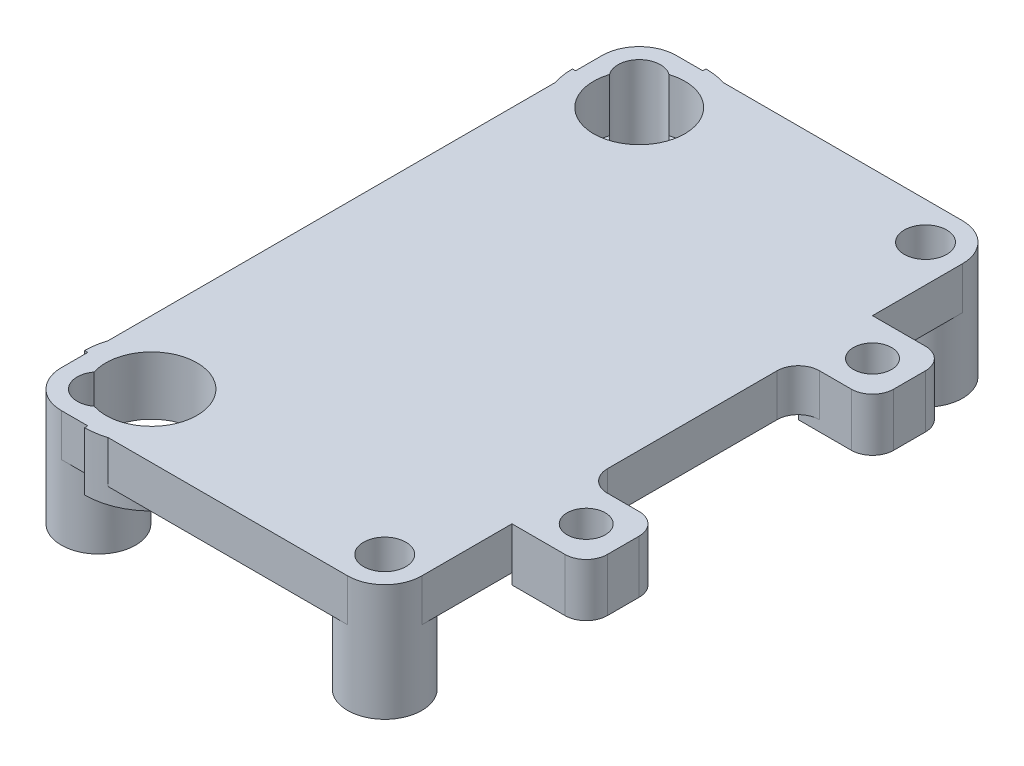
SolidWorks part; units mm, degrees
ref_plane "Front Plane" through (0, 0, 0) normal (0, 0, 1) x (1, 0, 0)
ref_plane "Top Plane" through (0, 0, 0) normal (0, 1, 0) x (1, 0, 0)
ref_plane "Right Plane" through (0, 0, 0) normal (1, 0, 0) x (0, 0, -1)
sketch "Sketch1" plane through (0, 0, 0) normal (0, 1, 0) x (1, 0, 0)
  line L1 (0, 0) -> (27, 0) construction
  line L2 (0, 0) -> (0, 51) construction
  line L3 (0, 51) -> (27, 51) construction
  line L4 (27, 0) -> (27, 51) construction
  circle A0 centre (0, 51) radius 3.5
  circle A1 centre (27, 51) radius 3.5
  circle A2 centre (27, 0) radius 3.5
  circle A3 centre (0, 0) radius 3.5
  dimension "D3" = 7
  dimension "D1" = 51
  dimension "D2" = 27
extrude "Boss-Extrude1" add sketch "Sketch1" along normal blind 11
sketch "Sketch2" plane through (0, 11, 0) normal (0, 1, 0) x (1, 0, 0)
  line L0 (27, 54.5) -> (0, 54.5)
  line L2 (-3.5, 51) -> (-3.5, 0)
  line L4 (0, -3.5) -> (27, -3.5)
  line L6 (30.5, 0) -> (30.5, 51)
  circle A0 centre (0, 0) radius 3.5 construction
  circle A1 centre (27, 0) radius 3.5 construction
  circle A2 centre (27, 51) radius 3.5 construction
  circle A3 centre (0, 51) radius 3.5 construction
  arc A4 (-3.5, 0) -> (0, -3.5) centre (0, 0) ccw
  arc A5 (27, -3.5) -> (30.5, 0) centre (27, 0) ccw
  arc A6 (30.5, 51) -> (27, 54.5) centre (27, 51) ccw
  arc A7 (0, 54.5) -> (-3.5, 51) centre (0, 51) ccw
extrude "Boss-Extrude2" add sketch "Sketch2" against normal blind 1
hole_wizard "Ø4.0mm Dowel Hole1" positions "Sketch4" profile "Sketch6" hole size "Ø4.0" standard "DIN" end condition through all
sketch "Sketch4" plane through (0, 0, 0) normal (0, -1, 0) x (-1, 0, 0)
  point P0 (-27, 51)
  point P3 (0, 51)
  point P6 (0, 0)
  point P9 (-27, 0)
sketch "Sketch6" plane through (27, 0, -51) normal (1, 0, 0) x (0, 0, -1)
  line L0 (0, 0) -> (0, 11)
  line L1 (0, 11) -> (2, 11)
  line L2 (2, 11) -> (2, 0)
  line L5 (2, 0) -> (0, 0)
  line L11 (0, -6.35) -> (0, 107.95) construction
  dimension "Thru Hole Dia." = 4
  dimension "Thru Hole Depth" = 11
sketch "Sketch10" plane through (0, 10, 0) normal (0, -1, 0) x (1, 0, 0)
  line L0 (0, 0) -> (27, -51) construction
  line L1 (27, 0) -> (0, -51) construction
  line L2 (26.1162, 0.4679) -> (-0.8838, -50.5321)
  line L3 (27.8838, -0.4679) -> (0.8838, -51.4679)
  line L4 (-0.8838, -0.4679) -> (26.1162, -51.4679)
  line L5 (0.8838, 0.4679) -> (27.8838, -50.5321)
  line L6 (-1.5, 0) -> (-1.5, -51)
  line L7 (0, -52.5) -> (27, -52.5)
  line L8 (28.5, -51) -> (28.5, 0)
  line L9 (27, 1.5) -> (0, 1.5)
  line L10 (-3.5, 0) -> (-3.5, -51)
  line L11 (27, 3.5) -> (0, 3.5)
  line L12 (30.5, -51) -> (30.5, 0)
  line L13 (0, -54.5) -> (27, -54.5)
  line L14 (-3.5, 0) -> (-3.5, -51)
  line L15 (27, 3.5) -> (0, 3.5)
  line L16 (30.5, -51) -> (30.5, 0)
  line L17 (0, -54.5) -> (27, -54.5)
  arc A0 (-1.5, -51) -> (0, -52.5) centre (0, -51) ccw
  arc A1 (27, -52.5) -> (28.5, -51) centre (27, -51) ccw
  arc A2 (28.5, 0) -> (27, 1.5) centre (27, 0) ccw
  arc A3 (0, 1.5) -> (-1.5, 0) centre (0, 0) ccw
  arc A4 (0, 3.5) -> (-3.5, 0) centre (0, 0) ccw
  arc A5 (30.5, 0) -> (27, 3.5) centre (27, 0) ccw
  arc A6 (27, -54.5) -> (30.5, -51) centre (27, -51) ccw
  arc A7 (-3.5, -51) -> (0, -54.5) centre (0, -51) ccw
  arc A8 (0, 3.5) -> (-3.5, 0) centre (0, 0) ccw
  arc A9 (30.5, 0) -> (27, 3.5) centre (27, 0) ccw
  arc A10 (27, -54.5) -> (30.5, -51) centre (27, -51) ccw
  arc A11 (-3.5, -51) -> (0, -54.5) centre (0, -51) ccw
  circle A12 centre (0, -51) radius 3.5 construction
  circle A13 centre (27, -51) radius 3.5 construction
  circle A14 centre (27, 0) radius 3.5 construction
  circle A15 centre (0, 0) radius 3.5 construction
  circle A16 centre (0, -51) radius 3.5
  circle A17 centre (27, -51) radius 3.5
  circle A18 centre (27, 0) radius 3.5
  circle A19 centre (0, 0) radius 3.5
  arc M19 (0, 3.5) -> (-3.5, 0) centre (0, 0) cw
  line M20 (-3.5, 0) -> (-3.5, -51)
  arc M21 (-3.5, -51) -> (0, -54.5) centre (0, -51) cw
  line M22 (0, -54.5) -> (27, -54.5)
  arc M23 (27, -54.5) -> (30.5, -51) centre (27, -51) cw
  line M24 (30.5, -51) -> (30.5, 0)
  arc M25 (30.5, 0) -> (27, 3.5) centre (27, 0) cw
  line M26 (27, 3.5) -> (0, 3.5)
  dimension "D1" = 1
  dimension "D2" = 1
  dimension "D3" = 1
  dimension "D4" = 1
  dimension "D5" = 0
  dimension "D6" = 2
extrude "Boss-Extrude3" add sketch "Sketch10" along normal blind 3 contours L6 M19 M20 M21 | L9 M25 M26 M19 | L5 L4 L2 M19 | L2 L5 L3 M25 | L8 M23 M24 M25 | L7 M21 M22 M23 | L5 L2 L4 L3 | L5 L3 L4 M23 | L4 L2 L3 M21
sketch "Sketch11" plane through (0, 7, 0) normal (0, -1, 0) x (1, 0, 0)
  line L0 (30.5, -8.5) -> (37.5, -8.5)
  line L1 (37.5, -8.5) -> (37.5, -15.5)
  line L2 (37.5, -15.5) -> (30.5, -15.5)
  line L3 (30.5, -51) -> (30.5, 0) construction
  line L5 (14.6315, -25.5) -> (41.7794, -25.5) construction
  line L6 (37.5, -35.5) -> (30.5, -35.5)
  line L7 (37.5, -42.5) -> (37.5, -35.5)
  line L8 (30.5, -42.5) -> (37.5, -42.5)
  line L9 (30.5, -35.5) -> (30.5, -42.5)
  line L10 (30.5, -8.5) -> (30.5, -15.5)
  line L11 (27, 3.5) -> (0, 3.5) construction
  dimension "D1" = 7
  dimension "D2" = 7
  dimension "D3" = 12
extrude "Boss-Extrude4" add sketch "Sketch11" against normal up to surface and the other way blind 1 up to face at (27, 11, -53)
fillet "Fillet1" radius 2 6 edges at (30.5, 9, -35.5) (37.5, 8.5, -42.5) (37.5, 8.5, -35.5) (37.5, 8.5, -15.5) (30.5, 9, -15.5) (37.5, 8.5, -8.5)
hole_wizard "M3 Clearance Hole1" positions "Sketch12" profile "Sketch13" hole size "M3" standard "DIN" end condition through all
sketch "Sketch12" plane through (0, 6, 0) normal (0, -1, 0) x (-1, 0, 0)
  line L8 (-37.5, 15.5) -> (-30.5, 15.5)
  line L9 (-37.5, 15.5) -> (-37.5, 8.5)
  line L10 (-37.5, 8.5) -> (-30.5, 8.5)
  line L11 (-30.5, 15.5) -> (-30.5, 8.5)
  line L12 (-37.5, 15.5) -> (-30.5, 8.5) construction
  line L13 (-37.5, 8.5) -> (-30.5, 15.5) construction
  line L14 (-37.5, 13.5) -> (-37.5, 10.5) construction
  line L15 (-30.5, 15.5) -> (-35.5, 15.5) construction
  line L16 (-35.5, 8.5) -> (-30.5, 8.5) construction
  line L17 (-12.3685, 25.5) -> (-51.4055, 25.5) construction
  line L19 (-37.5, 42.5) -> (-30.5, 35.5) construction
  line L20 (-37.5, 35.5) -> (-30.5, 42.5) construction
  line L21 (-30.5, 35.5) -> (-30.5, 42.5)
  line L22 (-37.5, 42.5) -> (-30.5, 42.5)
  line L23 (-37.5, 35.5) -> (-37.5, 42.5)
  line L24 (-37.5, 35.5) -> (-30.5, 35.5)
  point P68 (-34, 12)
  point P123 (-34, 39)
sketch "Sketch13" plane through (34, 6, -12) normal (1, 0, 0) x (0, 0, -1)
  line L0 (0, 0) -> (0, 5)
  line L1 (0, 5) -> (1.8, 5)
  line L2 (1.8, 5) -> (1.8, 0)
  line L5 (1.8, 0) -> (0, 0)
  line L11 (0, -6.35) -> (0, 107.95) construction
  dimension "Thru Hole Dia." = 3.6
  dimension "Thru Hole Depth" = 5
sketch "Sketch15" plane through (0, 11, 0) normal (0, 1, 0) x (1, 0, 0)
  line L0 (27, 54.5) -> (0, 54.5) construction
  line L1 (-3.5, 51) -> (-3.5, 0) construction
  line L2 (30.5, 25.5) -> (9.7647, 25.5) construction
  line L3 (30.5, 17.5) -> (30.5, 33.5) construction
  circle A0 centre (2.5, 48.5) radius 4.3
  circle A4 centre (2.5, 2.5) radius 4.3
  point P9 (0, 51)
  point P10 (-0.5406, 51.5406)
  dimension "D1" = 8.6
  dimension "D2" = 6
  dimension "D3" = 6
extrude "Cut-Extrude1" cut sketch "Sketch15" against normal blind 5
sketch "Sketch17" plane through (0, 10, 0) normal (0, -1, 0) x (1, 0, 0)
  line L0 (2.5, 1.8) -> (2.5, 3.8)
  line L1 (-1.8, -2.5) -> (-3.8, -2.5)
  line L2 (-1.8, -48.5) -> (-3.8, -48.5)
  line L3 (2.5, -52.8) -> (2.5, -54.8)
  arc A0 (0.597, -54.5057) -> (-3.5057, -50.403) centre (2.5, -48.5) ccw construction
  arc A1 (1.2011, -52.5991) -> (-1.5991, -49.7989) centre (2.5, -48.5) ccw construction
  arc A2 (-1.5991, -1.2011) -> (1.2011, 1.5991) centre (2.5, -2.5) ccw construction
  arc A3 (2.5, -52.8) -> (-1.8, -48.5) centre (2.5, -48.5) ccw
  arc A4 (-1.8, -2.5) -> (2.5, 1.8) centre (2.5, -2.5) ccw
  arc A5 (-3.8, -2.5) -> (2.5, 3.8) centre (2.5, -2.5) ccw
  arc A6 (2.5, -54.8) -> (-3.8, -48.5) centre (2.5, -48.5) ccw
  arc A7 (1.2011, -52.5991) -> (-1.5991, -49.7989) centre (2.5, -48.5) ccw construction
  arc A8 (-1.5991, -1.2011) -> (1.2011, 1.5991) centre (2.5, -2.5) ccw construction
  arc A9 (-3.5057, -0.597) -> (0.597, 3.5057) centre (2.5, -2.5) ccw construction
  dimension "D1" = 2
extrude "Boss-Extrude6" add sketch "Sketch17" along normal blind 5.5 from surface at -1 starting at face at (2.0632, 11, -48.9368)
